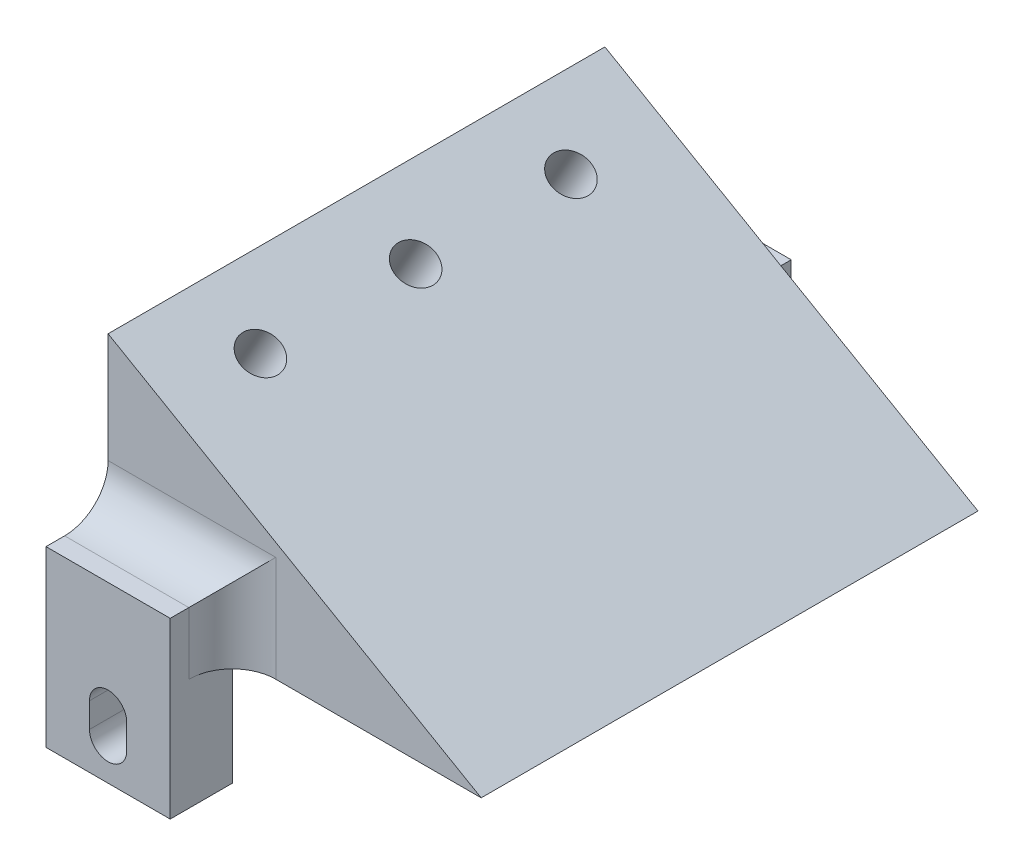
SolidWorks part; units mm, degrees
ref_plane "Front Plane" through (0, 0, 0) normal (0, 0, 1) x (1, 0, 0)
ref_plane "Top Plane" through (0, 0, 0) normal (0, 1, 0) x (1, 0, 0)
ref_plane "Right Plane" through (0, 0, 0) normal (1, 0, 0) x (0, 0, -1)
sketch "Sketch1" plane through (0, 0, 0) normal (0, 0, 1) x (1, 0, 0)
  line L0 (0, 0) -> (0, 34.6853)
  line L1 (0, 34.6853) -> (60.0768, 0)
  line L2 (60.0768, 0) -> (0, 0)
  dimension "D1" = 30
extrude "Boss-Extrude1" add sketch "Sketch1" along normal blind 80
sketch "Sketch2" plane through (0, 0, 80) normal (0, 0, 1) x (1, 0, 0)
  line L0 (0, 34.6853) -> (0, 0) construction
  line L1 (20, 10) -> (0, 10)
  line L2 (20, 10) -> (20, -18)
  line L3 (20, -18) -> (0, -18)
  line L4 (0, 10) -> (0, -18)
  line L5 (20, 10) -> (0, -18) construction
  line L6 (20, -18) -> (0, 10) construction
  line L7 (0, 0) -> (60.0768, 0) construction
  point P0 (10, -4)
  dimension "D1" = 0
  dimension "D2" = 20
  dimension "D3" = 10
  dimension "D4" = 18
extrude "Boss-Extrude2" add sketch "Sketch2" along normal blind 10
fillet "Fillet1" radius 7 2 edges at (20, 5, 80) (10, 10, 80)
sketch "Sketch3" plane through (0, 0, 90) normal (0, 0, 1) x (1, 0, 0)
  line L0 (27, 0) -> (60.0768, 0) construction
  line L1 (10, -12) -> (10, -8) construction
  line L2 (0, -8) -> (20, -8) construction
  line L3 (0, 10) -> (0, -18) construction
  line L4 (20, -18) -> (20, 10) construction
  line L5 (7, -12) -> (7, -8)
  line L6 (13, -12) -> (13, -8)
  arc A1 (7, -12) -> (13, -12) centre (10, -12) ccw
  arc A2 (13, -8) -> (7, -8) centre (10, -8) ccw
  point P11 (10, -10)
  dimension "D2" = 3
  dimension "D1" = 8
  dimension "D3" = 4
ref_plane "Plane1" through (0, 0, 40) normal (0, 0, -1) x (-1, 0, 0)
extrude "Cut-Extrude1" cut sketch "Sketch3" against normal blind 20
mirror "Mirror10" about plane through (0, 0, 40) normal (0, 0, -1) of "Cut-Extrude1", "Boss-Extrude2"
fillet "Fillet2" radius 7 2 edges at (20, 5, 0) (10, 10, 0)
sketch "Sketch4" plane through (15.0192, 26.014, 0) normal (0.5, 0.866, 0) x (0.866, -0.5, 0)
  line L0 (-6.3427, -65) -> (-6.3427, -15) construction
  line L1 (-17.3427, -80) -> (-17.3427, 0) construction
  line L2 (-17.3427, -40) -> (52.028, -40) construction
  line L3 (52.028, -80) -> (52.028, 0) construction
  circle A0 centre (-6.3427, -15) radius 3.2
  circle A1 centre (-6.3427, -40) radius 3.2
  circle A2 centre (-6.3427, -65) radius 3.2
  point P0 (-6.3427, -15)
  point P1 (-6.3427, -40)
  point P2 (-6.3427, -65)
  point P12 (-17.3427, -40)
  dimension "D2" = 6.4
  dimension "D5" = 6.4
  dimension "D6" = 6.4
  dimension "D1" = 50
  dimension "D3" = 11
  dimension "D4" = 11
extrude "Cut-Extrude2" cut sketch "Sketch4" against normal blind 9.5
equation "\"angle\"=30"
equation "\"D1@Sketch1\"=\"angle\""
